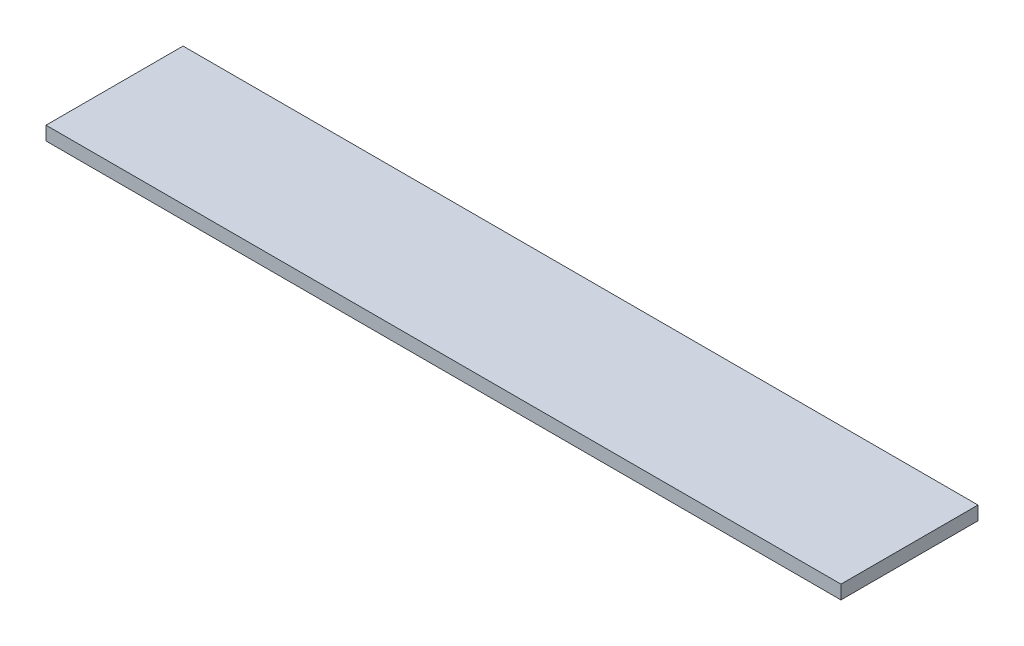
SolidWorks part; units mm, degrees
ref_plane "Front Plane" through (0, 0, 0) normal (0, 0, 1) x (1, 0, 0)
ref_plane "Top Plane" through (0, 0, 0) normal (0, 1, 0) x (1, 0, 0)
ref_plane "Right Plane" through (0, 0, 0) normal (1, 0, 0) x (0, 0, -1)
sketch "Sketch1" plane through (0, 0, 0) normal (0, 1, 0) x (1, 0, 0)
  line L0 (-47.625, 0) -> (47.625, 0) construction
  line L1 (-47.625, 7.9375) -> (47.625, 7.9375)
  line L2 (-47.625, -7.9375) -> (47.625, -7.9375)
  arc A0 (-47.625, 7.9375) -> (-47.625, -7.9375) centre (-47.625, 0) ccw
  arc A1 (47.625, -7.9375) -> (47.625, 7.9375) centre (47.625, 0) ccw
  point P3 (0, 0)
  dimension "D1" = 7.9375
  dimension "D2" = 95.25
extrude "Boss-Extrude1" add sketch "Sketch1" along normal blind 1.5875
sketch "Sketch2" plane through (0, 1.5875, 0) normal (0, 1, 0) x (1, 0, 0)
  line L0 (47.625, 7.9375) -> (-47.625, 7.9375) construction
  line L1 (-46.0375, 7.9375) -> (46.0375, 7.9375)
  line L2 (-46.0375, 7.9375) -> (-46.0375, -7.9375)
  line L3 (-46.0375, -7.9375) -> (46.0375, -7.9375)
  line L4 (46.0375, 7.9375) -> (46.0375, -7.9375)
  line L5 (-47.625, -7.9375) -> (47.625, -7.9375) construction
  line L7 (-68.0789, 19.2397) -> (64.0894, 19.2397)
  line L8 (-68.0789, 19.2397) -> (-68.0789, -20.3979)
  line L9 (-68.0789, -20.3979) -> (64.0894, -20.3979)
  line L10 (64.0894, 19.2397) -> (64.0894, -20.3979)
  dimension "D1" = 92.075
  dimension "D2" = 46.0375
extrude "Cut-Extrude1" cut sketch "Sketch2" against normal up to next
